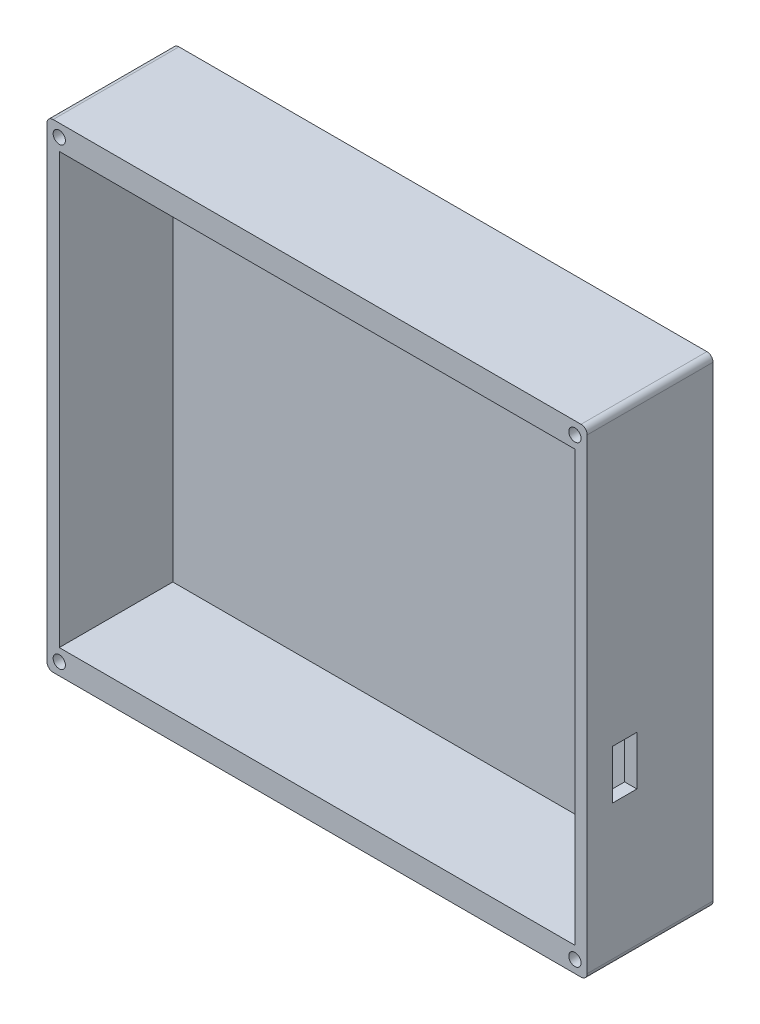
SolidWorks part; units mm, degrees
ref_plane "Front Plane" through (0, 0, 0) normal (0, 0, 1) x (1, 0, 0)
ref_plane "Top Plane" through (0, 0, 0) normal (0, 1, 0) x (1, 0, 0)
ref_plane "Right Plane" through (0, 0, 0) normal (1, 0, 0) x (0, 0, -1)
sketch "Sketch2" plane through (0, 0, 0) normal (0, 0, 1) x (1, 0, 0)
  line L1 (-44, 39) -> (44, 39)
  line L2 (-44, 39) -> (-44, -39)
  line L3 (-44, -39) -> (44, -39)
  line L4 (44, 39) -> (44, -39)
  line L5 (-44, 39) -> (44, -39) construction
  line L6 (-44, -39) -> (44, 39) construction
  point P0 (0, 0)
  dimension "D1" = 78
  dimension "D2" = 88
extrude "Boss-Extrude1" add sketch "Sketch2" along normal blind 20.5
sketch "Sketch5" plane through (0, 0, 20.5) normal (0, 0, 1) x (1, 0, 0)
  line L1 (-42, 35) -> (42, 35)
  line L2 (-42, 35) -> (-42, -35)
  line L3 (-42, -35) -> (42, -35)
  line L4 (42, 35) -> (42, -35)
  line L5 (-42, 35) -> (42, -35) construction
  line L6 (-42, -35) -> (42, 35) construction
  point P0 (0, 0)
  dimension "D1" = 84
  dimension "D2" = 70
extrude "Cut-Extrude1" cut sketch "Sketch5" against normal blind 18.5
sketch "Sketch6" plane through (44, 0, 0) normal (1, 0, 0) x (0, 0, -1)
  line L0 (-16.4, -8) -> (-12.4, -8) construction
  line L1 (-20.5, -39) -> (0, -39) construction
  line L2 (0, -8) -> (-16.4, -8) construction
  line L3 (0, -39) -> (0, 39) construction
  line L4 (-16.4, -8) -> (-16.4, -39) construction
  line L9 (-12.4, -8) -> (-12.4, -16) construction
  line L10 (-16.4, -16) -> (-12.4, -16) construction
  line L12 (-16.4, -8) -> (-12.4, -8)
  line L13 (-16.4, -8) -> (-16.4, -16)
  line L14 (-16.4, -16) -> (-12.4, -16)
  line L15 (-12.4, -8) -> (-12.4, -16)
  line L16 (-16.4, -8) -> (-12.4, -16) construction
  line L17 (-16.4, -16) -> (-12.4, -8) construction
  point P10 (-14.4, -12)
  point P12 (-14.4, -12)
extrude "Cut-Extrude2" cut sketch "Sketch6" against normal blind 18.5
sketch "Sketch7" plane through (0, 0, 20.5) normal (0, 0, 1) x (1, 0, 0)
  line L0 (-42, 35) -> (-42, 39) construction
  line L1 (44, 39) -> (-44, 39) construction
  line L2 (-42, 39) -> (-42, 37) construction
  line L3 (-44, 37) -> (-39.9678, 37) construction
  line L4 (-44, 39) -> (-44, -39) construction
  line L5 (-42, -35) -> (-42, -39) construction
  line L6 (-44, -39) -> (44, -39) construction
  line L7 (42, -35) -> (42, -39) construction
  line L8 (42, 35) -> (42, 39) construction
  circle A0 centre (-42, 37) radius 1
  circle A1 centre (-42, -37) radius 1
  circle A2 centre (42, -37) radius 1
  circle A3 centre (42, 37) radius 1
extrude "Cut-Extrude3" cut sketch "Sketch7" against normal blind 10
fillet "Fillet2" radius 1 4 edges at (-44, -39, 10.25) (44, -39, 10.25) (44, 39, 10.25) (-44, 39, 10.25)
